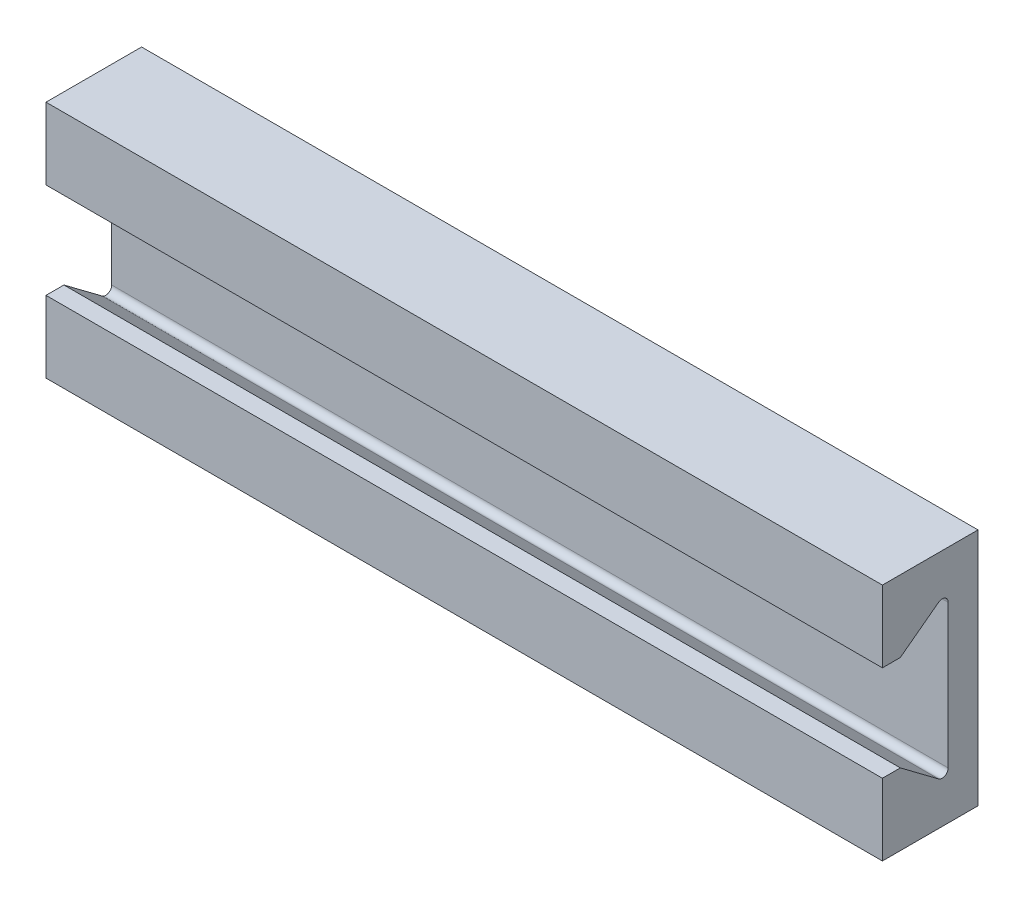
SolidWorks part; units mm, degrees
ref_plane "Front Plane" through (0, 0, 0) normal (0, 0, 1) x (1, 0, 0)
ref_plane "Top Plane" through (0, 0, 0) normal (0, 1, 0) x (1, 0, 0)
ref_plane "Right Plane" through (0, 0, 0) normal (1, 0, 0) x (0, 0, -1)
sketch "Sketch1" plane through (0, 0, 0) normal (0, 0, 1) x (1, 0, 0)
  line L1 (0, 0) -> (70, 0)
  line L2 (0, 0) -> (0, 20)
  line L3 (0, 20) -> (70, 20)
  line L4 (70, 0) -> (70, 20)
  dimension "D1" = 20
  dimension "D2" = 70
extrude "Boss-Extrude1" add sketch "Sketch1" along normal blind 8
sketch "Sketch2" plane through (70, 0, 0) normal (1, 0, 0) x (0, 0, -1)
  line L0 (-8, 6) -> (-6.5, 6)
  line L1 (-8, 0) -> (-8, 20) construction
  line L4 (-2.5, 3) -> (-2.5, 17)
  line L7 (-6.5, 14) -> (-8, 14)
  line L8 (-8, 0) -> (0, 0) construction
  line L9 (-8, 20) -> (0, 20) construction
  line L10 (-8, 6) -> (-8, 14)
  line L11 (-2.5, 3) -> (-6.5, 6)
  line L12 (-6.5, 14) -> (-2.5, 17)
  dimension "D1" = 6
  dimension "D2" = 1.5
  dimension "D3" = 5.5
  dimension "D4" = 3
  dimension "D5" = 6
  dimension "D6" = 1.5
  dimension "D7" = 3
extrude "Cut-Extrude1" cut sketch "Sketch2" against normal through all
fillet "Fillet1" radius 0.5 1 edges at (35, 3, 2.5)
fillet "Fillet2" radius 0.5 1 edges at (35, 17, 2.5)
